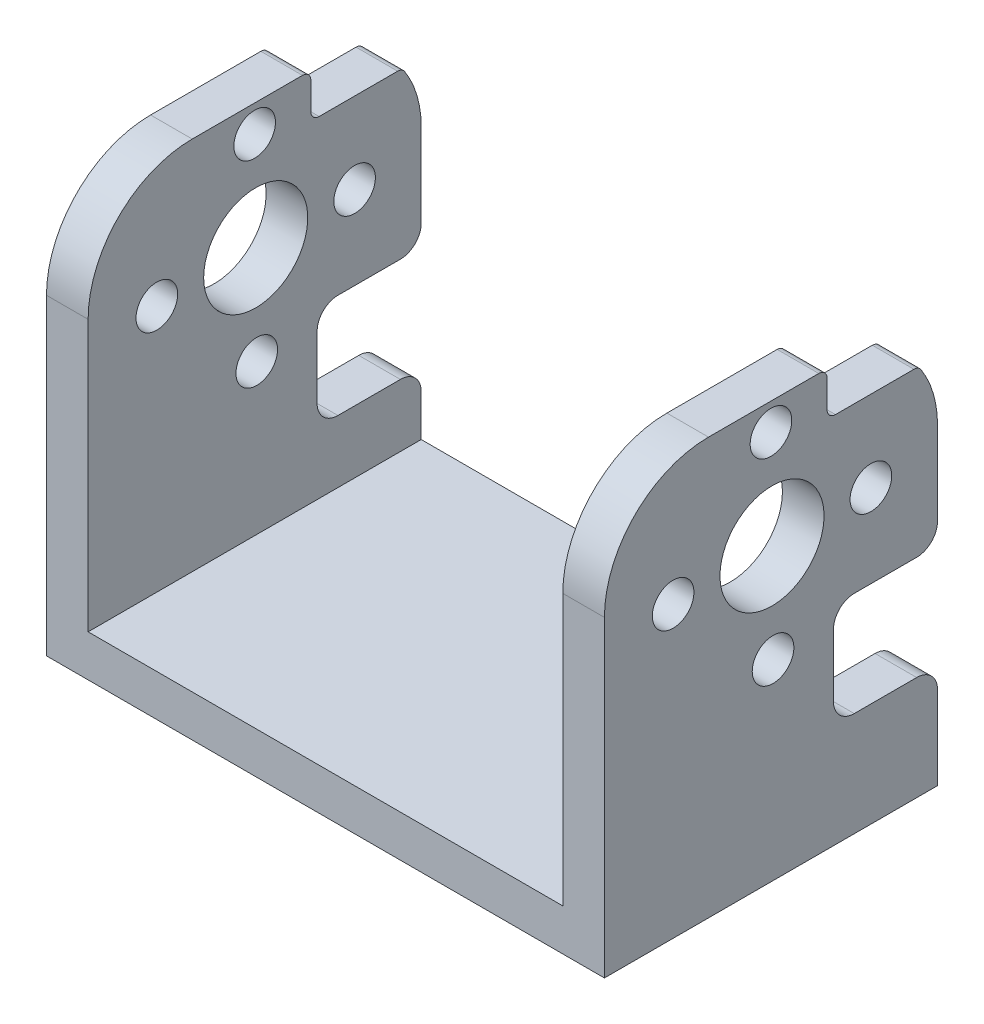
SolidWorks part; units mm, degrees
ref_plane "Front Plane" through (0, 0, 0) normal (0, 0, 1) x (1, 0, 0)
ref_plane "Top Plane" through (0, 0, 0) normal (0, 1, 0) x (1, 0, 0)
ref_plane "Right Plane" through (0, 0, 0) normal (1, 0, 0) x (0, 0, -1)
sketch "Sketch1" plane through (0, 0, 0) normal (0, 1, 0) x (1, 0, 0)
  line L1 (-17.018, -10.16) -> (17.018, -10.16)
  line L2 (-17.018, -10.16) -> (-17.018, 10.16)
  line L3 (-17.018, 10.16) -> (17.018, 10.16)
  line L4 (17.018, -10.16) -> (17.018, 10.16)
  line L5 (-17.018, -10.16) -> (17.018, 10.16) construction
  line L6 (-17.018, 10.16) -> (17.018, -10.16) construction
  point P0 (0, 0)
  dimension "D1" = 34.036
  dimension "D2" = 20.32
extrude "Boss-Extrude1" add sketch "Sketch1" along normal blind 25.4
sketch "Sketch2" plane through (0, 25.4, 0) normal (0, 1, 0) x (1, 0, 0)
  line L0 (-14.478, 10.16) -> (14.478, 10.16)
  line L1 (-14.478, 10.16) -> (-14.478, -10.16)
  line L2 (14.478, 10.16) -> (14.478, -10.16)
  line L3 (-14.478, -10.16) -> (14.478, -10.16)
  line L4 (17.018, 10.16) -> (-17.018, 10.16) construction
  line L6 (-17.018, 10.16) -> (-17.018, -10.16) construction
  line L7 (-17.018, -10.16) -> (17.018, -10.16) construction
  line L8 (17.018, -10.16) -> (17.018, 10.16) construction
  dimension "D1" = 2.54
  dimension "D2" = 2.54
extrude "Cut-Extrude1" cut sketch "Sketch2" against normal offset from surface (22.86 mm away) 2.54 up to face at (0, 0, 0)
sketch "Sketch3" plane through (-17.018, 0, 0) normal (-1, 0, 0) x (0, 0, 1)
  line L0 (0, 25.4) -> (0, 0) construction
  line L1 (-10.16, 25.4) -> (10.16, 25.4) construction
  line L2 (-7.874, 17.78) -> (7.874, 17.78) construction
  line L3 (-10.16, 0) -> (10.16, 0) construction
  circle A0 centre (-0.0635, 17.7165) radius 3.175
  circle A2 centre (0, 23.749) radius 1.27
  circle A3 centre (5.969, 17.653) radius 1.27
  circle A8 centre (0, 17.78) radius 7.874 construction
  circle A9 centre (-0.127, 11.684) radius 1.27
  circle A10 centre (-6.096, 17.78) radius 1.27
  point P18 (-0.0635, 17.7165)
  dimension "D2" = 15.748
  dimension "D3" = 5.969
  dimension "D1" = 2.54
  dimension "D5" = 6.096
  dimension "D6" = 17.78
  dimension "D7" = 6.35
  dimension "D4" = 4
extrude "Cut-Extrude2" cut sketch "Sketch3" against normal through all contours A2 | A10 | A9 | A3 | A0
sketch "Sketch4" plane through (0, 0, 0) normal (0, -1, 0) x (1, 0, 0)
  line L1 (-10.795, -9.525) -> (10.795, -9.525) construction
  line L2 (-10.795, -9.525) -> (-10.795, 9.525) construction
  line L3 (-10.795, 9.525) -> (10.795, 9.525) construction
  line L4 (17.018, -10.16) -> (17.018, 10.16)
  line L5 (17.018, 10.16) -> (-17.018, 10.16)
  line L6 (-17.018, 10.16) -> (-17.018, -10.16)
  line L7 (-17.018, -10.16) -> (17.018, -10.16)
  line L8 (17.018, -10.16) -> (17.018, 10.16) construction
  line L9 (17.018, 10.16) -> (-17.018, 10.16) construction
  line L10 (-17.018, 10.16) -> (-17.018, -10.16) construction
  line L11 (-17.018, -10.16) -> (17.018, -10.16) construction
  line L12 (10.795, -9.525) -> (10.795, 9.525) construction
  line L13 (-10.795, -9.525) -> (10.795, 9.525) construction
  line L14 (-10.795, 9.525) -> (10.795, -9.525) construction
  circle A0 centre (-10.795, 9.525) radius 1.778
  circle A1 centre (10.795, 9.525) radius 1.778
  circle A2 centre (10.795, -9.525) radius 1.778
  circle A3 centre (-10.795, -9.525) radius 1.778
  point P56 (0, 0)
  dimension "D4" = 3.556
  dimension "D2" = 19.05
  dimension "D3" = 21.59
  dimension "D1" = 0
fillet "Fillet2" radius 6.35 4 edges at (15.748, 25.4, -10.16) (15.748, 25.4, 10.16) (-15.748, 25.4, 10.16) (-15.748, 25.4, -10.16)
sketch "Sketch8" plane through (17.018, 0, 0) normal (1, 0, 0) x (0, 0, -1)
  line L0 (-10.16, 0) -> (10.16, 0) construction
  line L1 (10.16, 12.7) -> (3.81, 12.7)
  line L2 (10.16, 12.7) -> (10.16, 6.35)
  line L3 (10.16, 6.35) -> (3.81, 6.35)
  line L4 (3.81, 12.7) -> (3.81, 6.35)
  line L6 (10.16, 19.05) -> (10.16, 0) construction
  dimension "D1" = 6.35
  dimension "D2" = 6.35
  dimension "D3" = 6.35
extrude "Cut-Extrude5" cut sketch "Sketch8" against normal through all
fillet "Fillet4" radius 1.27 8 edges at (15.748, 6.35, -10.16) (15.748, 6.35, -3.81) (15.748, 12.7, -10.16) (15.748, 12.7, -3.81) (-15.748, 12.7, -10.16) (-15.748, 12.7, -3.81) (-15.748, 6.35, -3.81) (-15.748, 6.35, -10.16)
sketch "Sketch10" plane through (17.018, 0, 0) normal (1, 0, 0) x (0, 0, -1)
  line L5 (3.4254, 22.7182) -> (14.2025, 22.7182)
  line L6 (3.4254, 22.7182) -> (3.4254, 28.9358)
  line L7 (3.4254, 28.9358) -> (14.2025, 28.9358)
  line L8 (14.2025, 22.7182) -> (14.2025, 28.9358)
  line L9 (3.4254, 22.7182) -> (14.2025, 28.9358) construction
  line L10 (3.4254, 28.9358) -> (14.2025, 22.7182) construction
  point P0 (8.814, 25.827)
extrude "Cut-Extrude6" cut sketch "Sketch10" against normal through all
fillet "Fillet6" radius 0.508 6 edges at (-15.748, 22.7182, -8.9933) (-15.748, 22.7182, -3.4254) (-15.748, 25.4, -3.4254) (15.748, 22.7182, -8.9933) (15.748, 22.7182, -3.4254) (15.748, 25.4, -3.4254)
